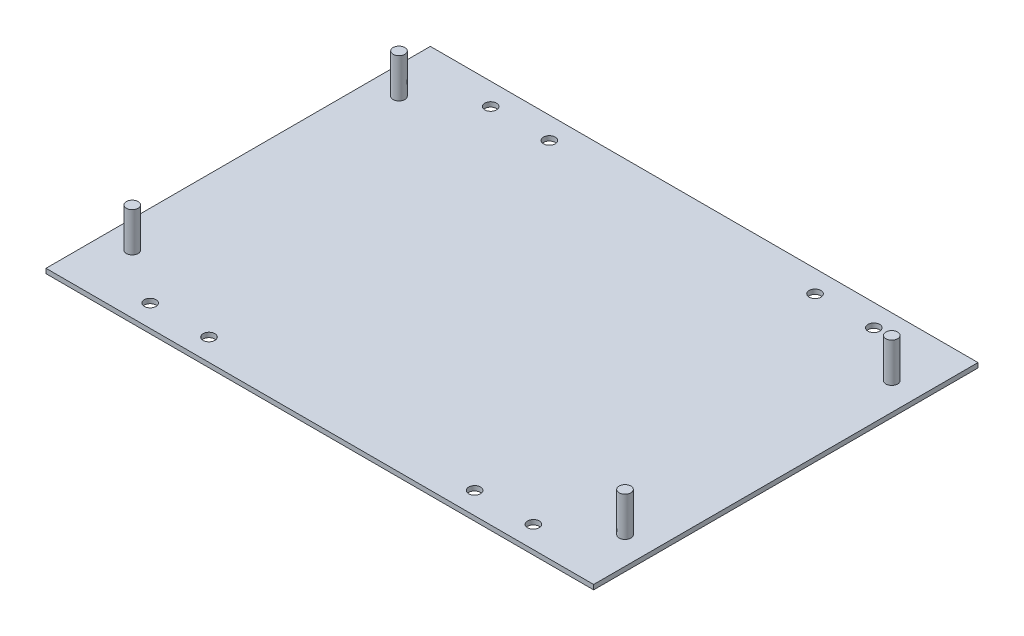
SolidWorks part; units mm, degrees
ref_plane "Front Plane" through (0, 0, 0) normal (0, 0, 1) x (1, 0, 0)
ref_plane "Top Plane" through (0, 0, 0) normal (0, 1, 0) x (1, 0, 0)
ref_plane "Right Plane" through (0, 0, 0) normal (1, 0, 0) x (0, 0, -1)
sketch "Sketch1" plane through (0, 0, 0) normal (0, 1, 0) x (1, 0, 0)
  line L1 (-69.85, -45.72) -> (69.85, -45.72)
  line L2 (-69.85, -45.72) -> (-69.85, 52.324)
  line L3 (-69.85, 52.324) -> (69.85, 52.324)
  line L4 (69.85, -45.72) -> (69.85, 52.324)
  circle A12 centre (-48.8772, -40.12) radius 1.5
  circle A13 centre (-33.8772, -40.12) radius 1.5
  circle A18 centre (-33.8912, 46.724) radius 1.5
  circle A19 centre (-48.8772, 46.724) radius 1.5
  circle A20 centre (33.8786, 46.724) radius 1.5
  circle A21 centre (48.8772, 46.724) radius 1.5
  circle A22 centre (33.8772, -40.12) radius 1.5
  circle A23 centre (48.8772, -40.12) radius 1.5
  point P0 (0, 0)
  dimension "D4" = 3
  dimension "D3" = 3
  dimension "D8" = 5.6
  dimension "D9" = 5.6
  dimension "D10" = 5.6
  dimension "D11" = 5.6
  dimension "D12" = 5.6
  dimension "D13" = 20.9728
  dimension "D1" = 139.7
  dimension "D2" = 98.044
  dimension "D5" = 15
  dimension "D6" = 20.9728
  dimension "D7" = 5.6
  dimension "D14" = 14.986
  dimension "D15" = 14.9986
  dimension "D16" = 15
  dimension "D17" = 20.9728
  dimension "D18" = 20.9728
extrude "Boss-Extrude1" add sketch "Sketch1" along normal blind 1.2
sketch "Sketch2" plane through (0, 1.2, 0) normal (0, 1, 0) x (1, 0, 0)
  line L2 (69.85, 52.324) -> (-69.85, 52.324) construction
  line L3 (-69.85, 52.324) -> (-69.85, -45.72) construction
  line L4 (-69.85, -45.72) -> (69.85, -45.72) construction
  circle A0 centre (-62.85, 37.324) radius 1.5
  circle A1 centre (-62.85, -30.72) radius 1.5
  circle A2 centre (62.85, -30.72) radius 1.5
  circle A3 centre (62.85, 37.324) radius 1.5
  dimension "D1" = 3
  dimension "D2" = 15
  dimension "D3" = 7
  dimension "D4" = 15
sketch "Sketch3" plane through (0, 1.2, 0) normal (0, 1, 0) x (1, 0, 0)
extrude "Boss-Extrude2" add sketch "Sketch2" along normal blind 10
